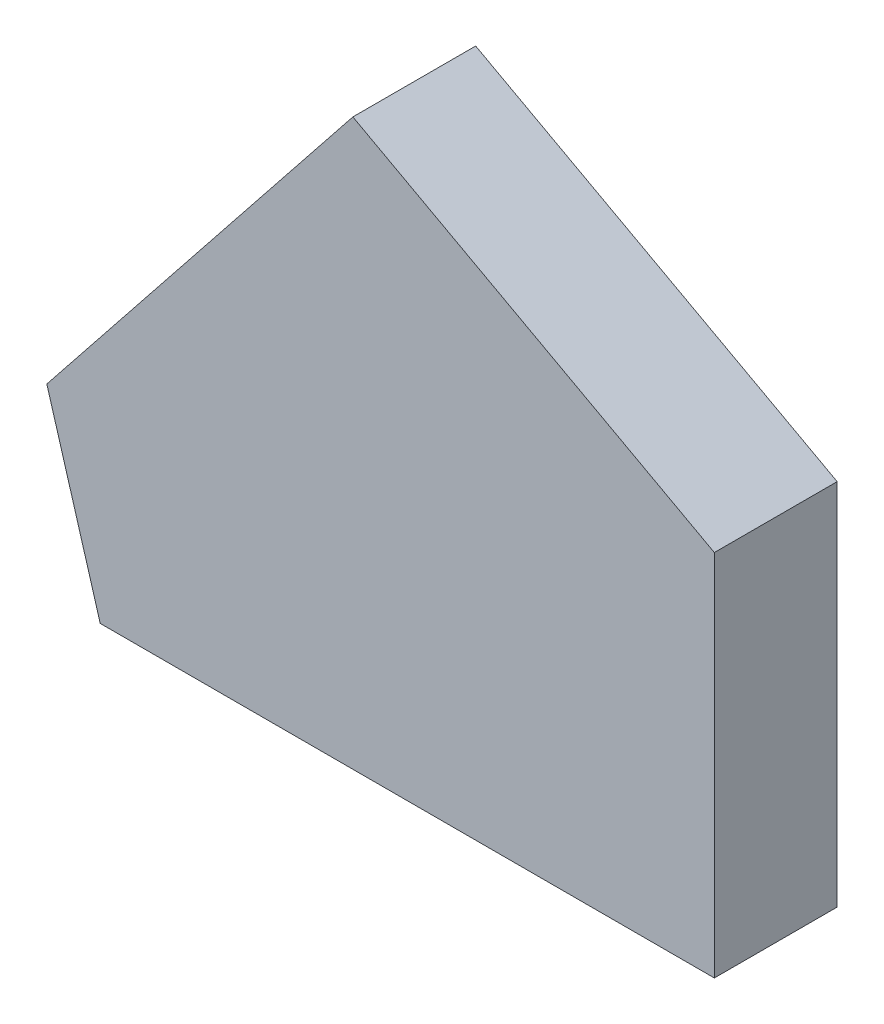
SolidWorks part; units mm, degrees
ref_plane "Alzado" through (0, 0, 0) normal (0, 0, 1) x (1, 0, 0)
ref_plane "Planta" through (0, 0, 0) normal (0, 1, 0) x (1, 0, 0)
ref_plane "Vista lateral" through (0, 0, 0) normal (1, 0, 0) x (0, 0, -1)
sketch "Croquis7" plane through (0, 0, 0) normal (0, 0, 1) x (1, 0, 0)
  line L0 (0, 0) -> (-50, 0)
  line L1 (-50, 0) -> (-54.3485, 14.7087)
  line L2 (-54.3485, 14.7087) -> (-29.4316, 46)
  line L3 (-29.4316, 46) -> (0, 30)
  line L4 (0, 30) -> (0, 0)
  dimension "D1" = 50
  dimension "D2" = 40
  dimension "D3" = 30
  dimension "D4" = 46
  dimension "D5" = 125
  dimension "D6" = 100
extrude "Saliente-Extruir2" add sketch "Croquis7" along normal blind 10 contours L4 L3 L2 L1 L0
